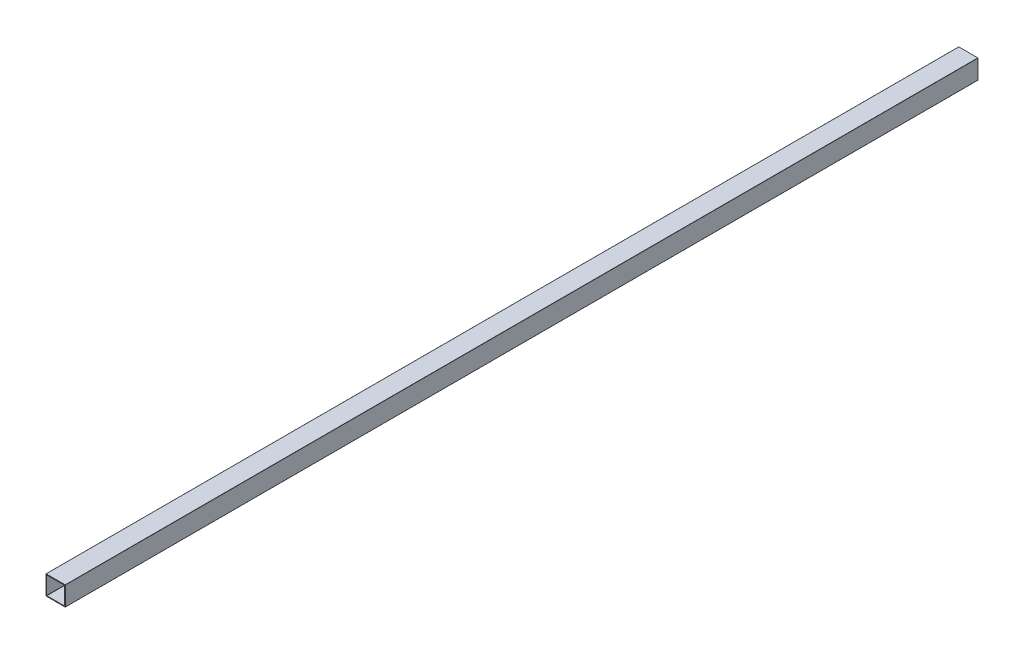
SolidWorks part; units mm, degrees
material "AISI 1035 Acero (SS)"
ref_plane "Alzado" through (0, 0, 0) normal (0, 0, 1) x (1, 0, 0)
ref_plane "Planta" through (0, 0, 0) normal (0, 1, 0) x (1, 0, 0)
ref_plane "Vista lateral" through (0, 0, 0) normal (1, 0, 0) x (0, 0, -1)
sketch "Croquis1" plane through (0, 0, 0) normal (0, 0, 1) x (1, 0, 0)
  line L0 (-58.95, -58.95) -> (-58.95, 58.95)
  line L1 (-63.5, -63.5) -> (63.5, -63.5)
  line L2 (-63.5, -63.5) -> (-63.5, 63.5)
  line L3 (-63.5, 63.5) -> (63.5, 63.5)
  line L4 (63.5, -63.5) -> (63.5, 63.5)
  line L5 (-63.5, -63.5) -> (63.5, 63.5) construction
  line L6 (-63.5, 63.5) -> (63.5, -63.5) construction
  line L7 (-58.95, 58.95) -> (58.95, 58.95)
  line L8 (58.95, -58.95) -> (58.95, 58.95)
  line L9 (-58.95, -58.95) -> (58.95, -58.95)
  point P0 (0, 0)
  dimension "D2" = 127
  dimension "D3" = 4.55
extrude "Saliente-Extruir1" add sketch "Croquis1" against normal blind 6000
fillet "Redondeo1" radius 1 8 edges at (-58.95, 58.95, -3000) (58.95, 58.95, -3000) (58.95, -58.95, -3000) (-63.5, -63.5, -3000) (-63.5, 63.5, -3000) (-58.95, -58.95, -3000) (63.5, -63.5, -3000) (63.5, 63.5, -3000)
